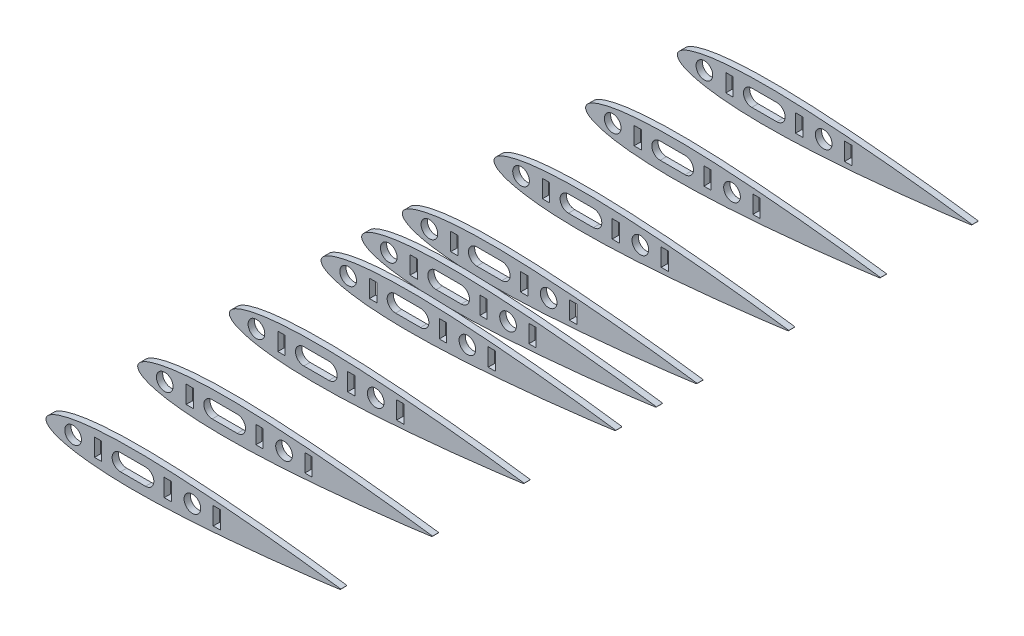
SolidWorks part; units mm, degrees
material "Balsa"
ref_plane "Front Plane" through (0, 0, 0) normal (1, 0, 0) x (0, 1, 0)
ref_plane "Top Plane" through (0, 0, 0) normal (0, 0, 1) x (0, 1, 0)
ref_plane "Right Plane" through (0, 0, 0) normal (0, 1, 0) x (-1, 0, 0)
curve "Curve1" [suppressed]
  spline degree 3 poles (0.0004, -0.0044, 0) (-0.0002, 0, 0) (0.0004, 0.0044, 0) (0.0023, 0.0087, 0) (0.0053, 0.0128, 0) (0.0094, 0.0167, 0) (0.0147, 0.0206, 0) (0.0211, 0.0243, 0) (0.0286, 0.0279, 0) (0.0372, 0.0313, 0) (0.0468, 0.0347, 0) (0.0576, 0.0378, 0) (0.0693, 0.0408, 0) (0.0821, 0.0436, 0) (0.0958, 0.0462, 0) (0.1104, 0.0486, 0) (0.126, 0.0507, 0) (0.1425, 0.0527, 0) (0.1597, 0.0544, 0) (0.1778, 0.056, 0) (0.1966, 0.0572, 0) (0.2162, 0.0583, 0) (0.2364, 0.0591, 0) (0.2572, 0.0596, 0) (0.2786, 0.06, 0) (0.3005, 0.0601, 0) (0.3228, 0.0599, 0) (0.3456, 0.0596, 0) (0.3688, 0.0591, 0) (0.3922, 0.0583, 0) (0.4159, 0.0574, 0) (0.4398, 0.0563, 0) (0.4638, 0.0551, 0) (0.4879, 0.0537, 0) (0.5121, 0.0522, 0) (0.5362, 0.0505, 0) (0.5602, 0.0488, 0) (0.5841, 0.0469, 0) (0.6078, 0.045, 0) (0.6313, 0.043, 0) (0.6544, 0.0409, 0) (0.6772, 0.0388, 0) (0.6995, 0.0367, 0) (0.7214, 0.0345, 0) (0.7428, 0.0324, 0) (0.7636, 0.0302, 0) (0.7838, 0.028, 0) (0.8033, 0.0259, 0) (0.8222, 0.0238, 0) (0.8402, 0.0217, 0) (0.8575, 0.0196, 0) (0.874, 0.0177, 0) (0.8895, 0.0158, 0) (0.9042, 0.014, 0) (0.9179, 0.0122, 0) (0.9307, 0.0106, 0) (0.9424, 0.0091, 0) (0.9531, 0.0077, 0) (0.9627, 0.0064, 0) (0.9713, 0.0052, 0) (0.9788, 0.0042, 0) (0.9851, 0.0033, 0) (0.9903, 0.0026, 0) (0.9944, 0.002, 0) (0.9973, 0.0017, 0) (0.999, 0.0013, 0) (1.0007, 0.0014, 0) (1.0007, -0.0014, 0) (0.999, -0.0013, 0) (0.9973, -0.0017, 0) (0.9944, -0.002, 0) (0.9903, -0.0026, 0) (0.9851, -0.0033, 0) (0.9788, -0.0042, 0) (0.9713, -0.0052, 0) (0.9627, -0.0064, 0) (0.9531, -0.0077, 0) (0.9424, -0.0091, 0) (0.9307, -0.0106, 0) (0.9179, -0.0122, 0) (0.9042, -0.014, 0) (0.8895, -0.0158, 0) (0.874, -0.0177, 0) (0.8575, -0.0196, 0) (0.8402, -0.0217, 0) (0.8222, -0.0238, 0) (0.8033, -0.0259, 0) (0.7838, -0.028, 0) (0.7636, -0.0302, 0) (0.7428, -0.0324, 0) (0.7214, -0.0345, 0) (0.6995, -0.0367, 0) (0.6772, -0.0388, 0) (0.6544, -0.0409, 0) (0.6313, -0.043, 0) (0.6078, -0.045, 0) (0.5841, -0.0469, 0) (0.5602, -0.0488, 0) (0.5362, -0.0505, 0) (0.5121, -0.0522, 0) (0.4879, -0.0537, 0) (0.4638, -0.0551, 0) (0.4398, -0.0563, 0) (0.4159, -0.0574, 0) (0.3922, -0.0583, 0) (0.3688, -0.0591, 0) (0.3456, -0.0596, 0) (0.3228, -0.0599, 0) (0.3005, -0.0601, 0) (0.2786, -0.06, 0) (0.2572, -0.0596, 0) (0.2364, -0.0591, 0) (0.2162, -0.0583, 0) (0.1966, -0.0572, 0) (0.1778, -0.056, 0) (0.1597, -0.0544, 0) (0.1425, -0.0527, 0) (0.126, -0.0507, 0) (0.1104, -0.0486, 0) (0.0958, -0.0462, 0) (0.0821, -0.0436, 0) (0.0693, -0.0408, 0) (0.0576, -0.0378, 0) (0.0468, -0.0347, 0) (0.0372, -0.0313, 0) (0.0286, -0.0279, 0) (0.0211, -0.0243, 0) (0.0147, -0.0206, 0) (0.0094, -0.0167, 0) (0.0053, -0.0128, 0) (0.0023, -0.0087, 0) (0.0004, -0.0044, 0) (-0.0002, 0, 0) (0.0004, 0.0044, 0) knots -0.006773 -0.004321 -0.002106 0 0.002106 0.004321 0.006773 0.009557 0.012734 0.016343 0.020406 0.024934 0.029933 0.035402 0.041337 0.047732 0.054575 0.061857 0.069565 0.077682 0.086195 0.095084 0.104333 0.113922 0.123829 0.134035 0.144516 0.155249 0.16621 0.177376 0.18872 0.200217 0.21184 0.223563 0.235359 0.2472 0.259058 0.270907 0.282718 0.294465 0.306118 0.317651 0.329037 0.340249 0.35126 0.362045 0.372579 0.382836 0.392793 0.402425 0.411711 0.420628 0.429156 0.437273 0.444962 0.452203 0.458979 0.465275 0.471075 0.476366 0.481134 0.485369 0.48906 0.492198 0.494776 0.496788 0.498228 0.499094 0.499383 0.500617 0.500906 0.501772 0.503212 0.505224 0.507802 0.51094 0.514631 0.518866 0.523634 0.528925 0.534725 0.541021 0.547797 0.555038 0.562727 0.570844 0.579372 0.588289 0.597575 0.607207 0.617164 0.627421 0.637955 0.64874 0.659751 0.670963 0.682349 0.693882 0.705535 0.717282 0.729093 0.740942 0.7528 0.764641 0.776437 0.78816 0.799783 0.81128 0.822624 0.83379 0.844751 0.855484 0.865965 0.876171 0.886078 0.895667 0.904916 0.913805 0.922318 0.930435 0.938143 0.945425 0.952268 0.958663 0.964598 0.970067 0.975066 0.979594 0.983657 0.987266 0.990443 0.993227 0.995679 0.997894 1 1.002106 1.004321 1.006773 periodic
sketch "Sketch1" plane through (0, 0, 0) normal (0, 0, 1) x (0, 1, 0)
  line L0 (0, 0) -> (0, -141.3129) construction
  line L1 (-4.25, -60.25) -> (4.25, -60.25)
  line L2 (-4.25, -26.75) -> (4.25, -26.75)
  line L3 (-4.25, -26.75) -> (-4.25, -23.25)
  line L4 (-4.25, -23.25) -> (4.25, -23.25)
  line L5 (4.25, -26.75) -> (4.25, -23.25)
  line L6 (-4.25, -26.75) -> (4.25, -23.25) construction
  line L7 (-4.25, -23.25) -> (4.25, -26.75) construction
  line L8 (-4.25, -60.25) -> (-4.25, -56.75)
  line L9 (-4.25, -56.75) -> (4.25, -56.75)
  line L10 (4.25, -60.25) -> (4.25, -56.75)
  line L11 (-4.25, -83.75) -> (4.25, -83.75)
  line L12 (-4.25, -83.75) -> (-4.25, -80.25)
  line L13 (-4.25, -80.25) -> (4.25, -80.25)
  line L14 (4.25, -83.75) -> (4.25, -80.25)
  line L15 (0, -47.75) -> (0, -35.75) construction
  line L16 (-4, -47.75) -> (-4, -35.75)
  line L17 (4, -47.75) -> (4, -35.75)
  arc A0 (-4, -47.75) -> (4, -47.75) centre (0, -47.75) ccw
  arc A1 (4, -35.75) -> (-4, -35.75) centre (0, -35.75) ccw
  circle A2 centre (0, -70.25) radius 4
  circle A3 centre (0, -13) radius 4
  spline S1 degree 3 poles (0.6196, -0.0582) (0, 0.0284) (-0.6196, -0.0582) (-1.2234, -0.3192) (-1.8045, -0.7457) (-2.3654, -1.3325) (-2.9082, -2.0777) (-3.4332, -2.9803) (-3.9401, -4.0389) (-4.4274, -5.2516) (-4.894, -6.6161) (-5.3381, -8.1294) (-5.758, -9.7882) (-6.1524, -11.5887) (-6.5195, -13.5268) (-6.858, -15.5981) (-7.1666, -17.7978) (-7.4441, -20.1207) (-7.6897, -22.5615) (-7.9025, -25.1144) (-8.0821, -27.7736) (-8.2283, -30.5328) (-8.341, -33.3855) (-8.4205, -36.3252) (-8.4672, -39.3449) (-8.4818, -42.4376) (-8.4652, -45.5962) (-8.4184, -48.8131) (-8.3428, -52.0809) (-8.2398, -55.392) (-8.1109, -58.7387) (-7.9577, -62.1131) (-7.7819, -65.5073) (-7.5855, -68.9135) (-7.3701, -72.3236) (-7.1376, -75.7298) (-6.8899, -79.124) (-6.6287, -82.4983) (-6.3559, -85.8449) (-6.0732, -89.1559) (-5.7824, -92.4237) (-5.485, -95.6405) (-5.1828, -98.7988) (-4.8774, -101.8914) (-4.5702, -104.9109) (-4.2628, -107.8503) (-3.9568, -110.7028) (-3.6535, -113.4616) (-3.3544, -116.1204) (-3.0609, -118.6729) (-2.7745, -121.1131) (-2.4965, -123.4355) (-2.2284, -125.6345) (-1.9714, -127.7049) (-1.727, -129.6421) (-1.4965, -131.4414) (-1.281, -133.0986) (-1.0819, -134.6099) (-0.9003, -135.9718) (-0.7372, -137.181) (-0.5939, -138.2349) (-0.4703, -139.1304) (-0.3703, -139.8671) (-0.2862, -140.4391) (-0.2385, -140.8548) (-0.1868, -141.0936) (-0.1915, -141.3386) (0.1915, -141.3386) (0.1868, -141.0936) (0.2385, -140.8548) (0.2862, -140.4391) (0.3703, -139.8671) (0.4703, -139.1304) (0.5939, -138.2349) (0.7372, -137.181) (0.9003, -135.9718) (1.0819, -134.6099) (1.281, -133.0986) (1.4965, -131.4414) (1.727, -129.6421) (1.9714, -127.7049) (2.2284, -125.6345) (2.4965, -123.4355) (2.7745, -121.1131) (3.0609, -118.6729) (3.3544, -116.1204) (3.6535, -113.4616) (3.9568, -110.7028) (4.2628, -107.8503) (4.5702, -104.9109) (4.8774, -101.8914) (5.1828, -98.7988) (5.485, -95.6405) (5.7824, -92.4237) (6.0732, -89.1559) (6.3559, -85.8449) (6.6287, -82.4983) (6.8899, -79.124) (7.1376, -75.7298) (7.3701, -72.3236) (7.5855, -68.9135) (7.7819, -65.5073) (7.9577, -62.1131) (8.1109, -58.7387) (8.2398, -55.392) (8.3428, -52.0809) (8.4184, -48.8131) (8.4652, -45.5962) (8.4818, -42.4376) (8.4672, -39.3449) (8.4205, -36.3252) (8.341, -33.3855) (8.2283, -30.5328) (8.0821, -27.7736) (7.9025, -25.1144) (7.6897, -22.5615) (7.4441, -20.1207) (7.1666, -17.7978) (6.858, -15.5981) (6.5195, -13.5268) (6.1524, -11.5887) (5.758, -9.7882) (5.3381, -8.1294) (4.894, -6.6161) (4.4274, -5.2516) (3.9401, -4.0389) (3.4332, -2.9803) (2.9082, -2.0777) (2.3654, -1.3325) (1.8045, -0.7457) (1.2234, -0.3192) (0.6196, -0.0582) (0, 0.0284) (-0.6196, -0.0582) knots -0.006773 -0.004321 -0.002106 0 0.002106 0.004321 0.006773 0.009557 0.012734 0.016343 0.020406 0.024934 0.029933 0.035402 0.041337 0.047732 0.054575 0.061857 0.069565 0.077682 0.086195 0.095084 0.104333 0.113922 0.123829 0.134035 0.144516 0.155249 0.16621 0.177376 0.18872 0.200217 0.21184 0.223563 0.235359 0.2472 0.259058 0.270907 0.282718 0.294465 0.306118 0.317651 0.329037 0.340249 0.35126 0.362045 0.372579 0.382836 0.392793 0.402425 0.411711 0.420628 0.429156 0.437273 0.444962 0.452203 0.458979 0.465275 0.471075 0.476366 0.481134 0.485369 0.48906 0.492198 0.494776 0.496788 0.498228 0.499094 0.499383 0.500617 0.500906 0.501772 0.503212 0.505224 0.507802 0.51094 0.514631 0.518866 0.523634 0.528925 0.534725 0.541021 0.547797 0.555038 0.562727 0.570844 0.579372 0.588289 0.597575 0.607207 0.617164 0.627421 0.637955 0.64874 0.659751 0.670963 0.682349 0.693882 0.705535 0.717282 0.729093 0.740942 0.7528 0.764641 0.776437 0.78816 0.799783 0.81128 0.822624 0.83379 0.844751 0.855484 0.865965 0.876171 0.886078 0.895667 0.904916 0.913805 0.922318 0.930435 0.938143 0.945425 0.952268 0.958663 0.964598 0.970067 0.975066 0.979594 0.983657 0.987266 0.990443 0.993227 0.995679 0.997894 1 1.002106 1.004321 1.006773 only from (0, 0) to (0, 0)
  point P2 (0, -25)
  point P12 (0, -56.75)
  point P17 (0, -80.25)
  point P19 (0, -41.75)
  dimension "D12" = 4
  dimension "D14" = 8
  dimension "D16" = 8
  dimension "D1" = 3.5
  dimension "D2" = 8.5
  dimension "D3" = 25
  dimension "D4" = 3.5
  dimension "D5" = 8.5
  dimension "D6" = 30
  dimension "D7" = 8.5
  dimension "D8" = 3.5
  dimension "D9" = 20
  dimension "D10" = 15
  dimension "D11" = 12
  dimension "D13" = 10
  dimension "D15" = 12
extrude "Boss-Extrude1" add sketch "Sketch1" along normal mid plane 3
pattern_linear "LPattern1" count 2 spacing 19.5 along (0, 0, 1) count 2 spacing 19.5 along (0, 0, -1) of bodies 101
pattern_linear "LPattern2" count 4 spacing 44 along (0, 0, -1) of bodies 103
pattern_linear "LPattern3" count 4 spacing 44 along (0, 0, 1) of bodies 102
